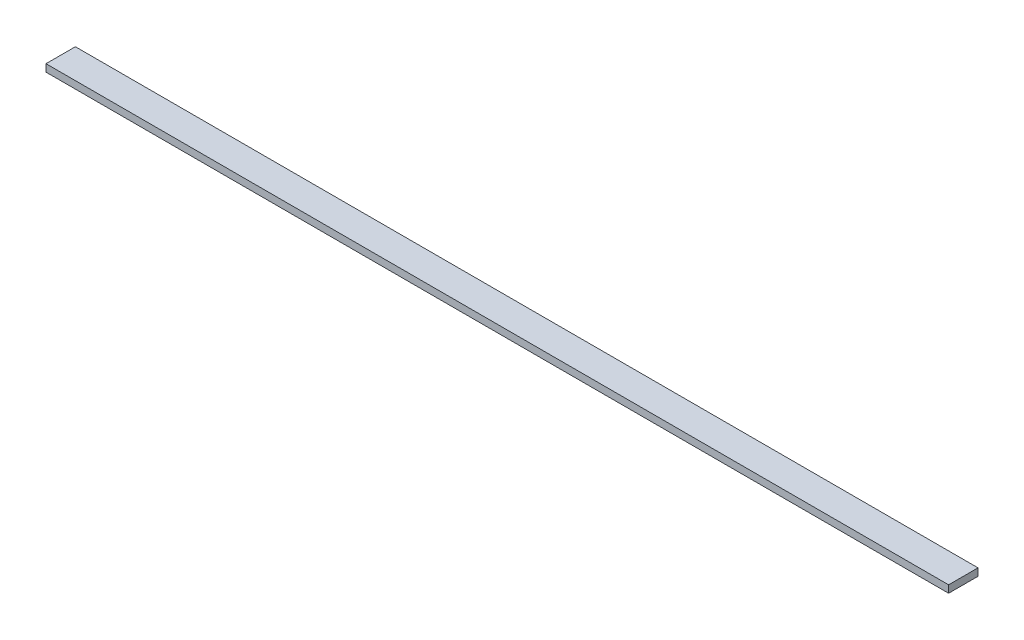
SolidWorks part; units mm, degrees
material "NEOPRENE"
ref_plane "Front Plane" through (0, 0, 0) normal (0, 0, 1) x (1, 0, 0)
ref_plane "Top Plane" through (0, 0, 0) normal (0, 1, 0) x (1, 0, 0)
ref_plane "Right Plane" through (0, 0, 0) normal (1, 0, 0) x (0, 0, -1)
sketch "Sketch1" plane through (0, 0, 0) normal (1, 0, 0) x (0, 0, -1)
  line L1 (-9.525, -2.3812) -> (9.525, -2.3812)
  line L2 (-9.525, -2.3812) -> (-9.525, 2.3813)
  line L3 (-9.525, 2.3813) -> (9.525, 2.3813)
  line L4 (9.525, -2.3812) -> (9.525, 2.3813)
  line L5 (-9.525, -2.3812) -> (9.525, 2.3813) construction
  line L6 (-9.525, 2.3813) -> (9.525, -2.3812) construction
  point P0 (0, 0)
  dimension "D1" = 4.7625
  dimension "D2" = 19.05
extrude "Boss-Extrude1" add sketch "Sketch1" along normal mid plane 585.1
